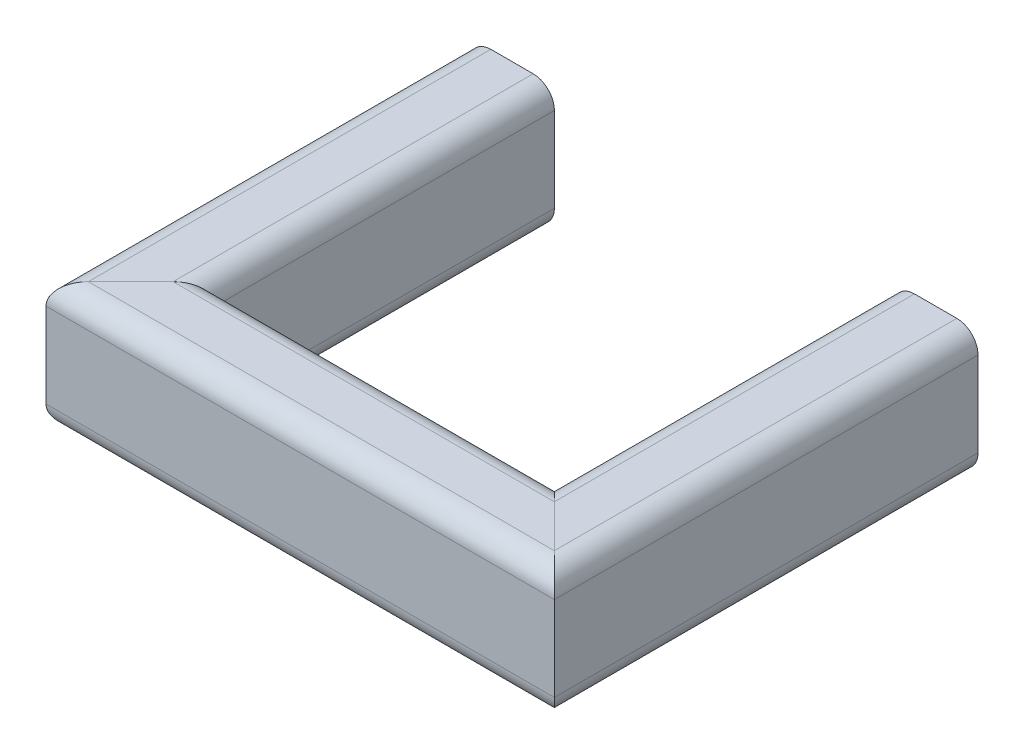
SolidWorks part; units mm, degrees
ref_plane "Front Plane" through (0, 0, 0) normal (0, 0, 1) x (1, 0, 0)
ref_plane "Top Plane" through (0, 0, 0) normal (0, 1, 0) x (1, 0, 0)
ref_plane "Right Plane" through (0, 0, 0) normal (1, 0, 0) x (0, 0, -1)
sketch "Sketch2" plane through (0, 0, 0) normal (0, 1, 0) x (1, 0, 0)
  line L0 (-101.6, 0) -> (101.6, 0)
  line L1 (-101.6, 0) -> (-101.6, 203.2)
  line L2 (101.6, 0) -> (101.6, 203.2)
  point P3 (0, 0)
  dimension "D1" = 203.2
  dimension "D2" = 203.2
  dimension "D3" = 203.2
other "Rectangular tube - configured 3 X 2 X 0.25(1)"
ref_plane "Plane1" through (127, 0, 0) normal (0, 0, -1) x (-1, 0, 0)
sketch "Sketch11" plane through (127, 0, 0) normal (0, 0, -1) x (-1, 0, 0)
  line L0 (-12.7, -31.75) -> (12.7, -31.75)
  line L1 (-19.05, -25.4) -> (-19.05, 25.4)
  line L2 (12.7, 31.75) -> (-12.7, 31.75)
  line L3 (19.05, 25.4) -> (19.05, -25.4)
  line L4 (-12.7, -38.1) -> (12.7, -38.1)
  line L5 (-25.4, -25.4) -> (-25.4, 25.4)
  line L6 (12.7, 38.1) -> (-12.7, 38.1)
  line L7 (25.4, 25.4) -> (25.4, -25.4)
  line L8 (0, 0) -> (25.4, 0) construction
  line L9 (0, 0) -> (0, 38.1) construction
  arc A0 (25.4, 25.4) -> (12.7, 38.1) centre (12.7, 25.4) ccw
  arc A1 (12.7, -38.1) -> (25.4, -25.4) centre (12.7, -25.4) ccw
  arc A2 (-25.4, -25.4) -> (-12.7, -38.1) centre (-12.7, -25.4) ccw
  arc A3 (-12.7, 38.1) -> (-25.4, 25.4) centre (-12.7, 25.4) ccw
  arc A4 (-12.7, 31.75) -> (-19.05, 25.4) centre (-12.7, 25.4) ccw
  arc A5 (19.05, 25.4) -> (12.7, 31.75) centre (12.7, 25.4) ccw
  arc A6 (12.7, -31.75) -> (19.05, -25.4) centre (12.7, -25.4) ccw
  arc A7 (-19.05, -25.4) -> (-12.7, -31.75) centre (-12.7, -25.4) ccw
  point P3 (0, -38.1)
  point P4 (-25.4, 0)
  point P5 (0, 0)
  point P6 (25.4, -38.1)
  point P7 (-25.4, -38.1)
  point P8 (-25.4, 38.1)
  point P33 (0, 0)
  point P35 (25.4, 38.1)
  point P36 (25.4, 0)
  point P37 (0, 38.1)
  dimension "D1" = 12.7
  dimension "Thickness" = 6.35
  dimension "V_leg" = 76.2
  dimension "H_leg" = 50.8
